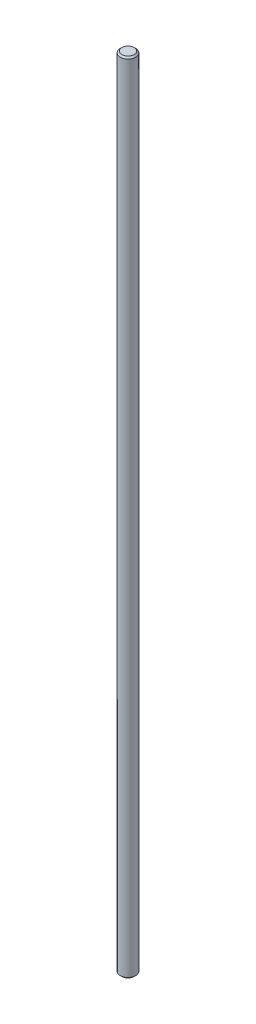
SolidWorks part; units mm, degrees
ref_plane "Front Plane" through (0, 0, 0) normal (0, 0, 1) x (1, 0, 0)
ref_plane "Top Plane" through (0, 0, 0) normal (0, 1, 0) x (1, 0, 0)
ref_plane "Right Plane" through (0, 0, 0) normal (1, 0, 0) x (0, 0, -1)
sketch "Sketch1" plane through (0, 0, 0) normal (0, 1, 0) x (1, 0, 0)
  circle A0 centre (0, 0) radius 5
  dimension "D1" = 10
extrude "Boss-Extrude1" add sketch "Sketch1" along normal mid plane 520
chamfer "Chamfer1" distance 1 angle 45 2 edges at (0, -260, 5) (0, 260, 5)
